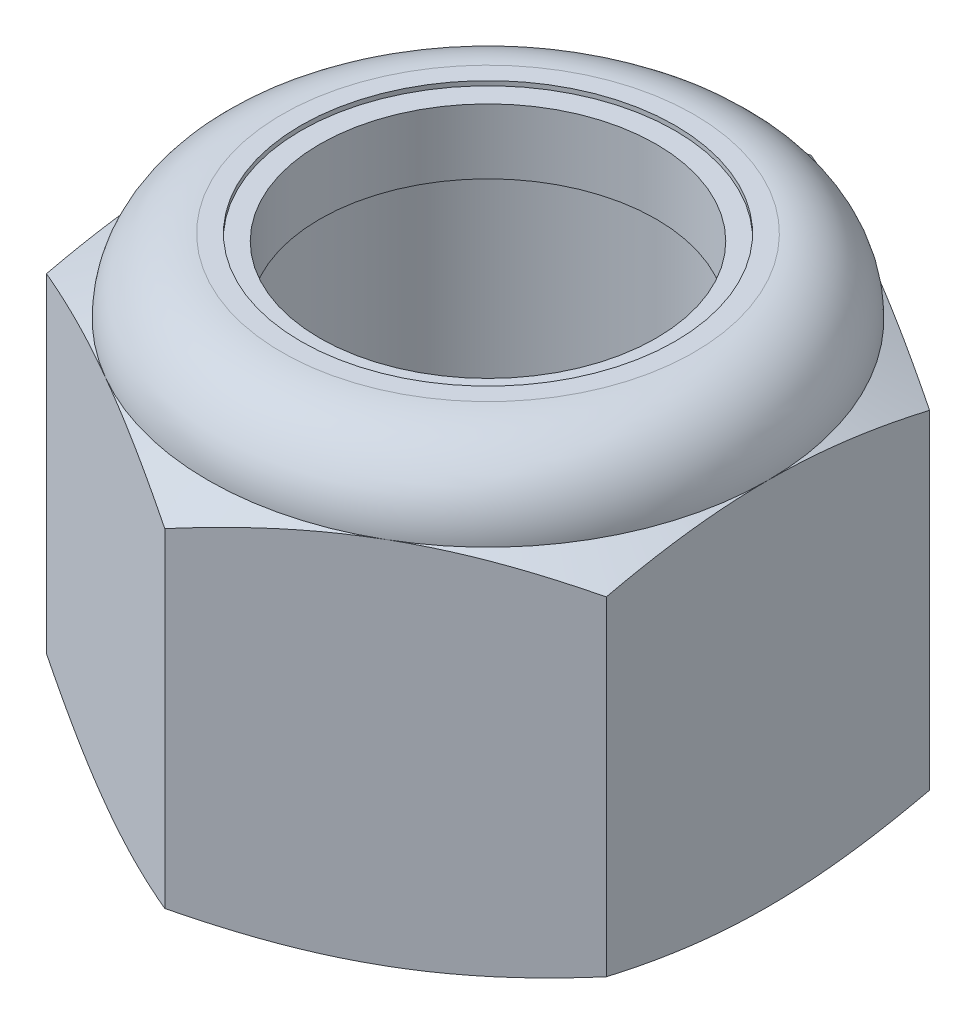
SolidWorks part; units mm, degrees
material "Plain Carbon Steel"
ref_plane "Front" through (0, 0, 0) normal (0, 0, 1) x (1, 0, 0)
ref_plane "Top" through (0, 0, 0) normal (0, 1, 0) x (1, 0, 0)
ref_plane "Right" through (0, 0, 0) normal (1, 0, 0) x (0, 0, -1)
sketch "Sketch1" plane through (0, 0, 0) normal (0, 1, 0) x (1, 0, 0)
  line L1 (0, 10.9985) -> (-9.525, 5.4993)
  line L2 (-9.525, 5.4993) -> (-9.525, -5.4993)
  line L3 (-9.525, -5.4993) -> (0, -10.9985)
  line L4 (0, -10.9985) -> (9.525, -5.4993)
  line L5 (9.525, -5.4993) -> (9.525, 5.4993)
  line L6 (9.525, 5.4993) -> (0, 10.9985)
  circle A0 centre (0, 0) radius 9.525 construction
  dimension "Hex Flats" = 19.05
extrude "Extrude1" add sketch "Sketch1" along normal blind 15.0812
sketch "Sketch2" plane through (0, 0, 0) normal (1, 0, 0) x (0, 0, -1)
  line L0 (-6.35, 0) -> (-6.35, 15.0812) construction
  line L1 (0, 0) -> (6.35, 0)
  line L2 (0, 0) -> (0, 15.0812)
  line L3 (0, 15.0812) -> (6.35, 15.0812)
  line L4 (6.35, 0) -> (6.35, 15.0812)
  line L5 (-5.4993, 15.0812) -> (5.4993, 15.0812) construction
  line L7 (0, -6.35) -> (0, 0) construction
  dimension "Thread Dia" = 12.7
revolve "Revolve1" add sketch "Sketch2" angle 360 about L7
sketch "Sketch3" plane through (0, 0, 0) normal (1, 0, 0) x (0, 0, -1)
  line L0 (6.35, 15.0813) -> (-6.35, 15.0812) construction
  line L1 (-6.35, 15.0812) -> (-6.35, 13.8113) construction
  line L2 (-6.35, 13.8113) -> (6.35, 15.0813) construction
  line L3 (6.35, 15.0813) -> (6.3658, 14.9233) construction
  line L4 (6.3658, 14.9233) -> (6.4764, 13.8176)
  line L5 (6.4764, 13.8176) -> (5.7529, 14.1441)
  line L6 (5.7529, 14.1441) -> (5.7213, 14.46)
  line L7 (5.7213, 14.46) -> (6.3658, 14.9233)
  line L8 (5.7371, 14.302) -> (6.4211, 14.3704) construction
  line L9 (6.35, 15.0813) -> (6.35, 14.3633) construction
  line L10 (6.35, 14.3633) -> (-6.35, 13.0933) construction
  line L11 (-6.35, 13.0933) -> (-6.35, 13.8113) construction
  line L12 (-0.1353, 15.0813) -> (0.1353, 12.3754) construction
  line L13 (-6.35, 0) -> (-6.35, 15.0812) construction
  line L14 (0, 15.0812) -> (6.35, 15.0812) construction
  line L15 (6.35, 0) -> (6.35, 15.0812) construction
  point P13 (0, 13.7283)
  dimension "D1" = 0.1588
  dimension "D2" = 0.3175
  dimension "Thread Pitch" = 1.27
  dimension "D4" = 60
  dimension "D5" = 1.27
revolve "Cut-Revolve1" [suppressed] cut sketch "Sketch3" angle 360 about L12
pattern_linear "LPattern1" [suppressed] count 12 spacing 1.27 along (0, 1, 0) count 2 spacing 1.27 along (0, 1, 0)
sketch "Sketch4" plane through (0, 0, 0) normal (1, 0, 0) x (0, 0, -1)
  line L0 (0, 15.0812) -> (6.35, 15.0812)
  line L1 (6.35, 15.0812) -> (5.7213, 14.7881)
  line L2 (5.7213, 14.7881) -> (5.7213, 0.2932)
  line L3 (5.7213, 0.2932) -> (6.35, 0)
  line L4 (6.35, 0) -> (0, 0)
  line L5 (0, 0) -> (0, 15.0812)
  line L6 (6.35, 0) -> (6.35, 15.0812) construction
  line L7 (0, 15.0812) -> (6.35, 15.0812) construction
  line L8 (0, 0) -> (6.35, 0) construction
  line L9 (0, 0) -> (0, 15.0812) construction
  line L10 (0, 15.0812) -> (0, 15.775) construction
  dimension "D1" = 25
revolve "Cut-Revolve2" cut sketch "Sketch4" angle 360 about L10
combine bodies "Combine1" operation type subtract main body 112 bodies to subtract 109
sketch "Sketch5" plane through (0, 0, 0) normal (1, 0, 0) x (0, 0, -1)
  line L0 (0, 0) -> (9.525, 0)
  line L1 (9.525, 0) -> (10.9985, 0.6871)
  line L2 (10.9985, 0.6871) -> (10.9985, 11.8806)
  line L3 (10.9985, 11.8806) -> (9.525, 12.5677)
  line L4 (7.0115, 15.0813) -> (7.0115, 16.3513)
  line L5 (7.0115, 16.3513) -> (12.2685, 16.3513)
  line L6 (12.2685, 16.3513) -> (12.2685, -1.27)
  line L7 (12.2685, -1.27) -> (0, -1.27)
  line L8 (0, -1.27) -> (0, 0)
  line L9 (9.525, 12.5677) -> (9.525, 0) construction
  line L10 (0, 0) -> (6.35, 0) construction
  line L13 (10.9985, 6.2839) -> (12.2685, 6.2839) construction
  line L14 (10.9985, 15.0812) -> (10.9985, 0) construction
  line L15 (0, 0) -> (0, 16.3513) construction
  line L20 (0, 16.3513) -> (7.0115, 16.3513) construction
  line L22 (0, 15.0812) -> (6.35, 15.0812) construction
  arc A0 (9.525, 12.5677) -> (7.0115, 15.0813) centre (7.0115, 12.5677) ccw
  dimension "D1" = 25
  dimension "D2" = 1.27
  dimension "D3" = 15.0813
  dimension "D4" = 2.5135
revolve "Cut-Revolve3" cut sketch "Sketch5" angle 360 about L15
sketch "Sketch6" plane through (0, 0, 0) normal (1, 0, 0) x (0, 0, -1)
  line L0 (0, 12.5677) -> (9.3726, 12.5677)
  line L1 (7.0115, 14.9289) -> (6.3664, 14.9289)
  line L2 (0, 16.3513) -> (0, 12.5677)
  line L3 (6.3664, 16.3513) -> (0, 16.3513)
  line L4 (0, 16.3513) -> (7.0115, 16.3513) construction
  line L5 (0, 0) -> (0, 16.3513) construction
  line L6 (0, 16.3513) -> (0, 44.323) construction
  line L7 (6.3664, 14.9289) -> (6.3664, 16.3513)
  line L8 (7.0115, 15.0813) -> (7.0115, 14.9289) construction
  line L9 (6.3664, 14.9289) -> (5.7213, 14.9289) construction
  line L10 (5.7213, 14.9289) -> (5.7213, 14.7881) construction
  arc A0 (9.3726, 12.5677) -> (7.0115, 14.9289) centre (7.0115, 12.5677) ccw
  arc A1 (9.525, 12.5677) -> (7.0115, 15.0813) centre (7.0115, 12.5677) ccw construction
  dimension "D1" = 0.1524
revolve "Cut-Revolve4" cut sketch "Sketch6" angle 360 about L6
sketch "Sketch7" plane through (0, 0, 0) normal (1, 0, 0) x (0, 0, -1)
  line L0 (5.7213, 12.6439) -> (9.2951, 12.6439)
  line L1 (7.0115, 14.8527) -> (5.7213, 14.8527)
  line L2 (5.7213, 14.8527) -> (5.7213, 12.6439)
  line L3 (5.7213, 12.6439) -> (0, 12.6439) construction
  line L4 (0, 12.6439) -> (0, 14.8527) construction
  line L5 (0, 14.8527) -> (5.7213, 14.8527) construction
  line L6 (5.7213, 12.6439) -> (5.7213, 12.5677) construction
  line L7 (0, 12.5677) -> (9.3726, 12.5677) construction
  line L8 (7.0115, 14.8527) -> (7.0115, 14.9289) construction
  arc A0 (9.2951, 12.6439) -> (7.0115, 14.8527) centre (7.0115, 12.5677) ccw
  arc A2 (9.3726, 12.5677) -> (7.0115, 14.9289) centre (7.0115, 12.5677) ccw construction
  dimension "D1" = 0.0762
revolve "Revolve2" add sketch "Sketch7" angle 360 about L4
equation "\"D1@Sketch3\"=\"Thread Pitch@Sketch3\"/8"
equation "\"D2@Sketch3\"=\"Thread Pitch@Sketch3\"/4"
equation "\"D5@Sketch3\"=\"Thread Pitch@Sketch3\""
equation "\"D4@LPattern1\"=\"Thread Pitch@Sketch3\""
equation "\"D3@LPattern1\"=\"Thread Pitch@Sketch3\""
equation "\"D1@LPattern1\"=\"Height@Extrude1\"/\"Thread Pitch@Sketch3\""
equation "\"D4@Sketch5\"=\"Height@Extrude1\"/6"
